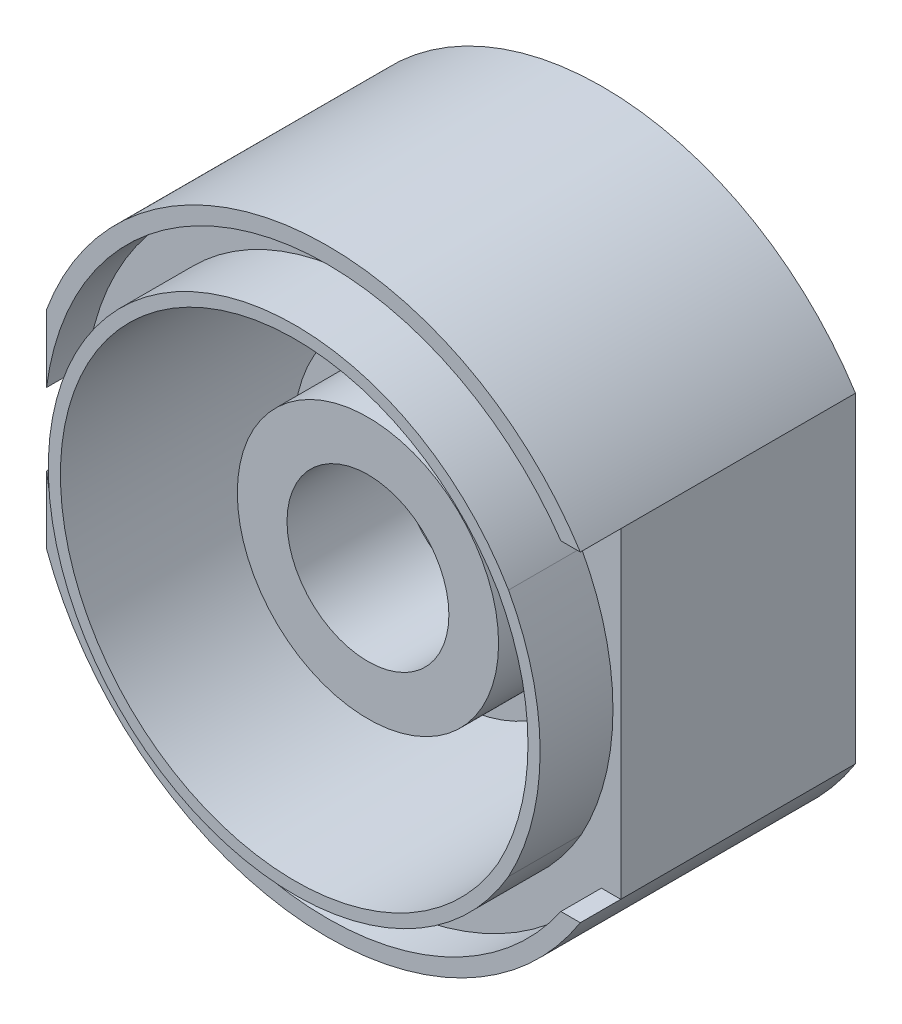
SolidWorks part; units mm, degrees
ref_plane "Front Plane" through (0, 0, 0) normal (0, 0, 1) x (1, 0, 0)
ref_plane "Top Plane" through (0, 0, 0) normal (0, 1, 0) x (1, 0, 0)
ref_plane "Right Plane" through (0, 0, 0) normal (1, 0, 0) x (0, 0, -1)
sketch "Sketch1" plane through (0, 0, 0) normal (0, 0, 1) x (1, 0, 0)
  line L0 (17.8759, 9.9153) -> (17.8759, -9.9153)
  arc A0 (17.8759, 9.9153) -> (17.8759, -9.9153) centre (2.2574, 0) ccw
extrude "Boss-Extrude1" add sketch "Sketch1" along normal blind 17
sketch "Sketch4" plane through (0, 0, 17) normal (0, 0, 1) x (1, 0, 0)
  line L2 (16.8759, -9.6203) -> (16.8759, 9.6203)
  line L3 (16.8759, -9.6203) -> (16.8759, 9.6203)
  arc A2 (16.8759, 9.6203) -> (16.8759, -9.6203) centre (2.2574, 0) ccw
  arc A3 (16.8759, 9.6203) -> (16.8759, -9.6203) centre (2.2574, 0) ccw
  dimension "D1" = 1
extrude "Cut-Extrude1" cut sketch "Sketch4" against normal blind 2.5
sketch "Sketch5" plane through (17.8759, 0, 0) normal (1, 0, 0) x (0, 0, -1)
  line L0 (-17, 9.9153) -> (-14.5, 9.9153)
  line L1 (-17, 9.9153) -> (0, 9.9153) construction
  line L2 (-14.5, 9.9153) -> (-14.5, -9.9153)
  line L3 (-17, -9.9153) -> (0, -9.9153) construction
  line L4 (-14.5, -9.9153) -> (-17, -9.9153)
  line L5 (-17, -9.9153) -> (-17, 9.9153)
extrude "Cut-Extrude2" cut sketch "Sketch5" against normal blind 2.5
sketch "Sketch6" plane through (0, 0, 14.5) normal (0, 0, 1) x (1, 0, 0)
  line L3 (15.6259, 7.6653) -> (15.4409, 7.6653)
  line L4 (15.4409, -7.6653) -> (15.6259, -7.6653)
  line L5 (15.6259, -7.6653) -> (15.6259, 7.6653)
  arc A1 (15.4409, 7.6653) -> (15.4409, -7.6653) centre (1.3758, 0) cw
  arc A2 (15.4409, 7.6653) -> (15.4409, -7.6653) centre (2.2574, 0) ccw
  arc A3 (15.4409, 7.6653) -> (15.4409, -7.6653) centre (2.2574, 0) ccw
  dimension "D1" = 2.25
extrude "Extrude-Thin1" add sketch "Sketch6" along normal blind 4.5 thin
sketch "Sketch8" plane through (0, 0, 0) normal (0, 0, -1) x (-1, 0, 0)
  line L0 (-2.2574, 18.5) -> (-2.2574, -18.5) construction
  arc A1 (-17.8759, -9.9153) -> (-17.8759, 9.9153) centre (-2.2574, 0) ccw construction
  circle A2 centre (-2.2574, 0) radius 8.5
  dimension "D1" = 17
extrude "Cut-Extrude4" cut sketch "Sketch8" against normal blind 6.5
sketch "Sketch9" plane through (0, 0, 6.5) normal (0, 0, -1) x (-1, 0, 0)
  circle A0 centre (-2.2574, 0) radius 5
  dimension "D1" = 10
extrude "Cut-Extrude5" cut sketch "Sketch9" against normal blind 27.5
sketch "Sketch10" plane through (0, 0, 6.5) normal (0, 0, -1) x (-1, 0, 0)
  circle A2 centre (-2.2574, 0) radius 6
  circle A3 centre (-2.2574, 0) radius 6
  dimension "D1" = 1
extrude "Cut-Extrude6" cut sketch "Sketch10" along normal blind 0.5 and the other way blind 1
sketch "Sketch14" plane through (0, 0, 14.5) normal (0, 0, 1) x (1, 0, 0)
  circle A2 centre (2.2574, 0) radius 9.5712
  arc A4 (14.7873, 7.2972) -> (14.7873, -7.2972) centre (2.2574, 0) ccw
  arc A11 (14.7873, 7.2972) -> (14.7873, -7.2972) centre (2.2574, 0) ccw
  arc A12 (14.7873, -7.2972) -> (14.7873, 7.2972) centre (1.3758, 0) ccw
  arc A13 (14.7873, -7.2972) -> (14.7873, 7.2972) centre (1.3758, 0) ccw
  dimension "D1" = 0
extrude "Cut-Extrude7" cut sketch "Sketch14" against normal blind 12.5
sketch "Sketch12" plane through (0, 0, 14.5) normal (0, 0, 1) x (1, 0, 0)
  circle A1 centre (2.2574, 0) radius 8.0712
  circle A2 centre (2.2574, 0) radius 8.0712
  dimension "D1" = 1.5
extrude "Cut-Extrude-Thin1" cut sketch "Sketch12" against normal blind 5 thin
sketch "Sketch15" plane through (0, 0, 0) normal (0, 0, 1) x (1, 0, 0)
  line L1 (-17.6886, 8.1082) -> (-15.1001, 8.1082)
  line L2 (-17.6886, 8.1082) -> (-17.6886, -9.0822)
  line L3 (-17.6886, -9.0822) -> (-15.1001, -9.0822)
  line L4 (-15.1001, 8.1082) -> (-15.1001, -9.0822)
  line L5 (-17.6886, 8.1082) -> (-15.1001, -9.0822) construction
  line L6 (-17.6886, -9.0822) -> (-15.1001, 8.1082) construction
  point P4 (-16.3943, -0.487)
extrude "Cut-Extrude8" cut sketch "Sketch15" along normal blind 31.5
